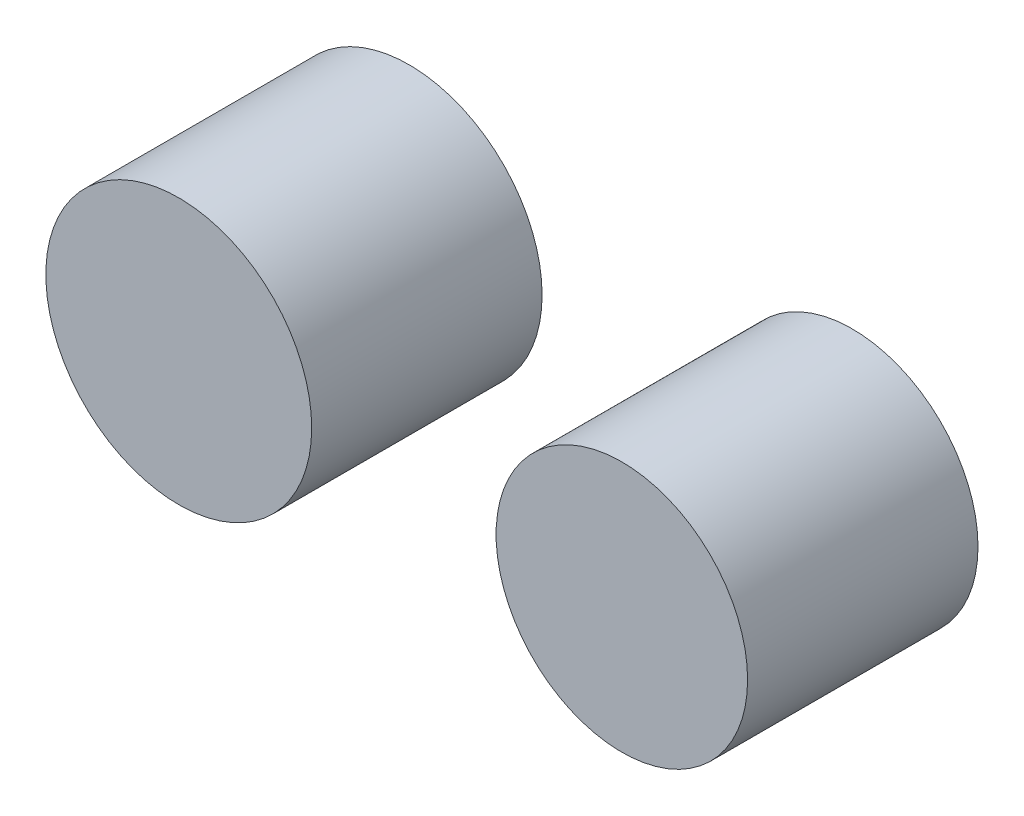
SolidWorks part; units mm, degrees
ref_plane "Ebene vorne" through (0, 0, 0) normal (0, 0, 1) x (1, 0, 0)
ref_plane "Ebene oben" through (0, 0, 0) normal (0, 1, 0) x (1, 0, 0)
ref_plane "Ebene rechts" through (0, 0, 0) normal (1, 0, 0) x (0, 0, -1)
sketch "Skizze1" plane through (0, 0, 0) normal (0, 0, 1) x (1, 0, 0)
  circle A0 centre (0, 0) radius 1.5
  circle A1 centre (5, 0) radius 1.4191
  dimension "D1" = 3
  dimension "D2" = 5
extrude "Aufsatz-Linear austragen1" add sketch "Skizze1" along normal blind 2.6
